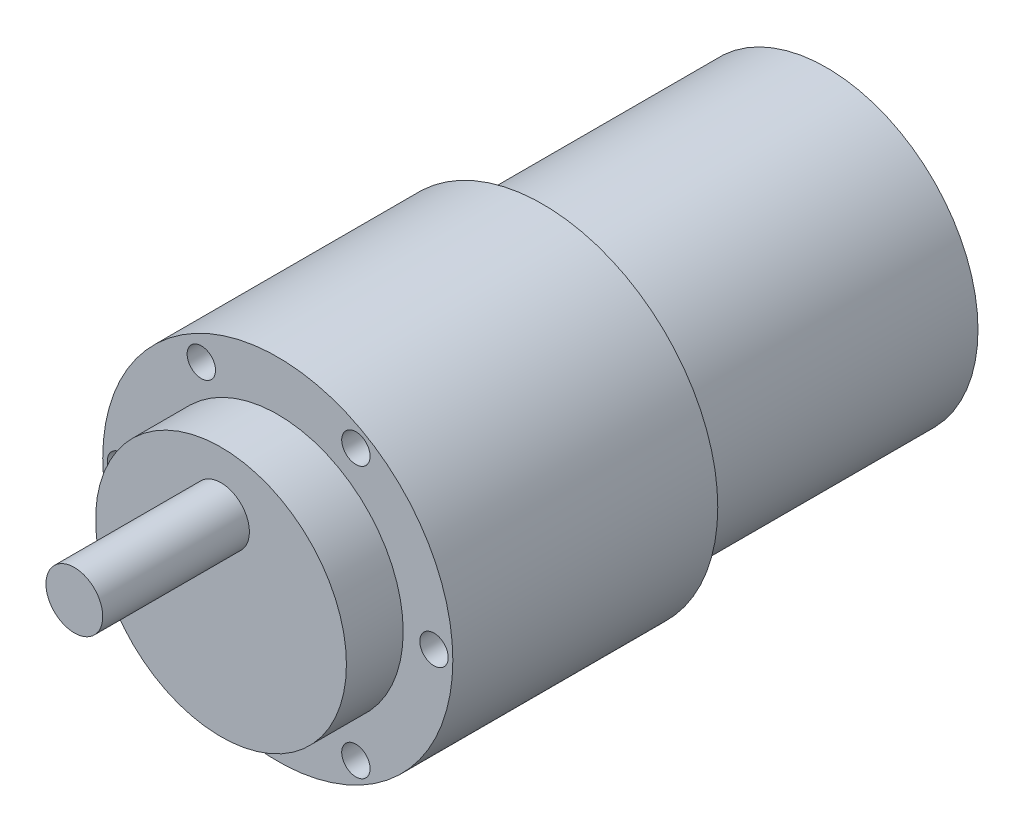
SolidWorks part; units mm, degrees
ref_plane "Front Plane" through (0, 0, 0) normal (0, 0, 1) x (1, 0, 0)
ref_plane "Top Plane" through (0, 0, 0) normal (0, 1, 0) x (1, 0, 0)
ref_plane "Right Plane" through (0, 0, 0) normal (1, 0, 0) x (0, 0, -1)
sketch "Sketch1" plane through (0, 0, 0) normal (0, 0, 1) x (1, 0, 0)
  circle A0 centre (0, 0) radius 16
  dimension "D1" = 32
extrude "Boss-Extrude1" add sketch "Sketch1" along normal blind 30
sketch "Sketch2" plane through (0, 0, 30) normal (0, 0, 1) x (1, 0, 0)
  circle A0 centre (0, 0) radius 18.5
  dimension "D1" = 37
extrude "Boss-Extrude2" add sketch "Sketch2" along normal blind 28
sketch "Sketch3" plane through (0, 0, 58) normal (0, 0, 1) x (1, 0, 0)
  line L0 (0, 0) -> (9.25, 16.0215) construction
  line L1 (9.25, 16.0215) -> (0, 0) construction
  line L2 (16.51, 0) -> (0, 0) construction
  line L3 (0, 0) -> (8.0735, -13.9836) construction
  line L4 (8.0735, -13.9836) -> (0, 0) construction
  line L5 (0, 0) -> (-8.2589, -14.3049) construction
  line L6 (0, 0) -> (-8.0792, 13.9936) construction
  line L7 (0, 0) -> (-16.51, 0) construction
  circle A0 centre (0, 7) radius 6 construction
  circle A1 centre (16.51, 0) radius 1.5 construction
  circle A2 centre (-16.51, 0) radius 1.5 construction
  circle A3 centre (0, 0) radius 18.5 construction
  circle A4 centre (8.255, -14.2981) radius 1.5 construction
  circle A5 centre (8.255, 14.2981) radius 1.5 construction
  circle A6 centre (0, 0) radius 13.2554
  point P18 (-8.255, -14.2981)
  point P19 (-8.255, 14.2981)
  point P21 (0, 0)
  point P22 (0, 0)
  dimension "D1" = 12
  dimension "D5" = 3
  dimension "D8" = 3
  dimension "D9" = 3
  dimension "D11" = 3
  dimension "D13" = 26.5108
  dimension "D14" = 60
  dimension "D2" = 7
  dimension "D3" = 60
  dimension "D4" = 60
  dimension "D6" = 16.51
  dimension "D7" = 16.51
  dimension "D10" = 16.51
  dimension "D12" = 16.51
  dimension "D15" = 60
  dimension "D16" = 16.51
  dimension "D17" = 16.51
extrude "Boss-Extrude3" add sketch "Sketch3" along normal blind 6
sketch "Sketch4" plane through (0, 0, 64) normal (0, 0, 1) x (1, 0, 0)
  circle A0 centre (0, 7) radius 3
  point P3 (0, 0)
  dimension "D1" = 6
  dimension "D2" = 7
extrude "Boss-Extrude4" add sketch "Sketch4" along normal blind 15.5
hole_wizard "Ø3.0 (3) Diameter Hole2" positions "Sketch9" profile "Sketch10" hole size "Ø3.0" standard "ANSI Metric"
sketch "Sketch9" plane through (0, 0, 58) normal (0, 0, 1) x (1, 0, 0)
  point P0 (-8.0792, 13.9936)
  point P3 (-16.51, 0)
  point P6 (8.255, -14.2981)
  point P9 (-8.255, -14.2981)
  point P12 (8.255, 14.2981)
  point P15 (16.51, 0)
sketch "Sketch10" plane through (-8.0792, 13.9936, 58) normal (1, 0, 0) x (0, -1, 0)
  line L0 (0, 0) -> (0, 4.4573)
  line L1 (0, 4.4573) -> (1.5, 3.556)
  line L2 (1.5, 3.556) -> (1.5, 0)
  line L5 (1.5, 0) -> (0, 0)
  line L10 (0, 4.4573) -> (-1.5, 3.556) construction
  line L11 (0, -6.35) -> (0, 107.95) construction
  dimension "Hole Dia." = 3
  dimension "Hole Depth" = 3.556
  dimension "Drill Angle" = 118
hole_wizard "Ø3.0 (3) Diameter Hole1" positions "Sketch5" profile "Sketch6" hole size "Ø3.0" standard "AS"
sketch "Sketch5" plane through (0, 0, 58) normal (0, 0, 1) x (1, 0, 0)
  point P0 (-16.51, 0)
  point P3 (8.255, -14.2981)
  point P6 (16.51, 0)
  point P9 (8.255, 14.2981)
sketch "Sketch6" plane through (-16.51, 0, 58) normal (1, 0, 0) x (0, -1, 0)
  line L0 (0, 0) -> (0, 4.4013)
  line L1 (0, 4.4013) -> (1.5, 3.5)
  line L2 (1.5, 3.5) -> (1.5, 0)
  line L5 (1.5, 0) -> (0, 0)
  line L10 (0, 4.4013) -> (-1.5, 3.5) construction
  line L11 (0, -6.35) -> (0, 107.95) construction
  dimension "Hole Dia." = 3
  dimension "Hole Depth" = 3.5
  dimension "Drill Angle" = 118
